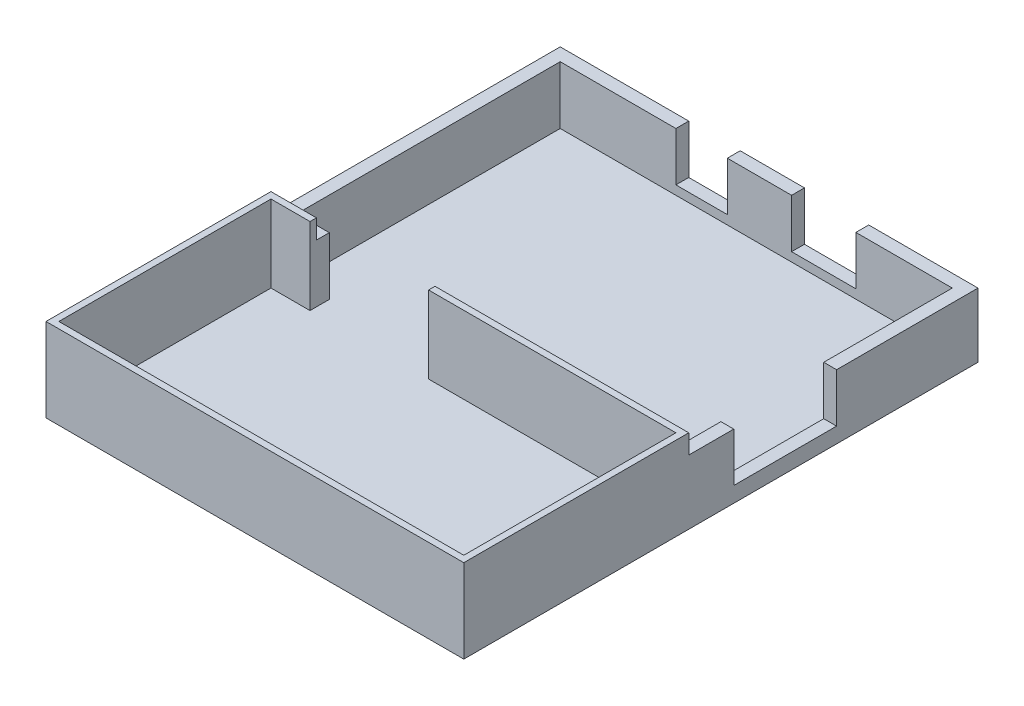
SolidWorks part; units mm, degrees
ref_plane "Front Plane" through (0, 0, 0) normal (0, 0, 1) x (1, 0, 0)
ref_plane "Top Plane" through (0, 0, 0) normal (0, 1, 0) x (1, 0, 0)
ref_plane "Right Plane" through (0, 0, 0) normal (1, 0, 0) x (0, 0, -1)
sketch "Sketch1" plane through (0, 0, 0) normal (0, 1, 0) x (1, 0, 0)
  line L1 (-30.5, -20.5) -> (30.5, -20.5)
  line L2 (-30.5, -20.5) -> (-30.5, 20.5)
  line L3 (-30.5, 20.5) -> (30.5, 20.5)
  line L4 (30.5, -20.5) -> (30.5, 20.5)
  line L5 (-30.5, -20.5) -> (30.5, 20.5) construction
  line L6 (-30.5, 20.5) -> (30.5, -20.5) construction
  point P0 (0, 0)
  dimension "D1" = 61
  dimension "D2" = 41
extrude "Boss-Extrude1" add sketch "Sketch1" along normal blind 1
sketch "Sketch2" plane through (0, 0, 0) normal (0, -1, 0) x (1, 0, 0)
  line L0 (-32.5, -22.5) -> (32.5, -22.5)
  line L1 (32.5, -22.5) -> (32.5, 22.5)
  line L2 (32.5, 22.5) -> (-32.5, 22.5)
  line L3 (-32.5, 22.5) -> (-32.5, -22.5)
  line L4 (30.5, -20.5) -> (30.5, 20.5)
  line L5 (30.5, 20.5) -> (-30.5, 20.5)
  line L6 (-30.5, 20.5) -> (-30.5, -20.5)
  line L7 (-30.5, -20.5) -> (30.5, -20.5)
  line L8 (30.5, -20.5) -> (30.5, 20.5)
  line L9 (30.5, 20.5) -> (-30.5, 20.5)
  line L10 (-30.5, 20.5) -> (-30.5, -20.5)
  line L11 (-30.5, -20.5) -> (30.5, -20.5)
  dimension "D1" = 0
  dimension "D2" = 2
extrude "Boss-Extrude2" add sketch "Sketch2" against normal blind 10
sketch "Sketch3" plane through (0, 10, 0) normal (0, 1, 0) x (1, 0, 0)
  line L0 (-32.5, 22.5) -> (32.5, 22.5) construction
  line L1 (-12.5, 22.5) -> (-4.5, 22.5)
  line L2 (-12.5, 22.5) -> (-12.5, 20.5)
  line L3 (-12.5, 20.5) -> (-4.5, 20.5)
  line L4 (-4.5, 22.5) -> (-4.5, 20.5)
  line L5 (-30.5, 20.5) -> (30.5, 20.5) construction
  line L7 (5.5, 22.5) -> (15.5, 22.5)
  line L8 (5.5, 22.5) -> (5.5, 20.5)
  line L9 (5.5, 20.5) -> (15.5, 20.5)
  line L10 (15.5, 22.5) -> (15.5, 20.5)
  line L11 (32.5, 22.5) -> (32.5, -22.5) construction
  line L12 (32.5, -15.5) -> (30.5, -15.5)
  line L13 (32.5, -15.5) -> (32.5, 0.5)
  line L14 (32.5, 0.5) -> (30.5, 0.5)
  line L15 (30.5, -15.5) -> (30.5, 0.5)
  line L16 (30.5, 20.5) -> (30.5, -20.5) construction
  line L17 (30.5, -20.5) -> (-30.5, -20.5) construction
  line L18 (-30.5, -20.5) -> (-30.5, 20.5) construction
  dimension "D1" = 10
  dimension "D2" = 36
  dimension "D3" = 8
  dimension "D4" = 18
  dimension "D5" = 5
  dimension "D6" = 16
extrude "Cut-Extrude1" cut sketch "Sketch3" against normal offset from surface (7.6 mm away) 1.4 up to face at (0, 1, 0)
sketch "Sketch4" plane through (0, 0, 22.5) normal (0, 0, 1) x (1, 0, 0)
  line L0 (32.5, 10) -> (32.5, 0) construction
  line L1 (-32.5, 0) -> (32.5, 0)
  line L2 (-32.5, 0) -> (-32.5, 1)
  line L3 (-32.5, 1) -> (32.5, 1)
  line L4 (32.5, 0) -> (32.5, 1)
  dimension "D1" = 1
extrude "Boss-Extrude3" add sketch "Sketch4" along normal blind 35
sketch "Sketch5" plane through (0, 1, 0) normal (0, 1, 0) x (1, 0, 0)
  line L0 (-31.5, -23.5) -> (-31.5, -56.5)
  line L1 (-31.5, -56.5) -> (31.5, -56.5)
  line L2 (31.5, -56.5) -> (31.5, -23.5)
  line L3 (31.5, -23.5) -> (-31.5, -23.5)
  line L4 (32.5, -22.5) -> (-32.5, -22.5)
  line L5 (-32.5, -22.5) -> (-32.5, -57.5)
  line L6 (-32.5, -57.5) -> (32.5, -57.5)
  line L7 (32.5, -57.5) -> (32.5, -22.5)
  line L8 (32.5, -22.5) -> (-32.5, -22.5)
  line L9 (-32.5, -22.5) -> (-32.5, -57.5)
  line L10 (-32.5, -57.5) -> (32.5, -57.5)
  line L11 (32.5, -57.5) -> (32.5, -22.5)
  dimension "D1" = 0
  dimension "D2" = 1
extrude "Boss-Extrude4" add sketch "Sketch5" along normal blind 12
sketch "Sketch6" plane through (0, 13, 0) normal (0, 1, 0) x (1, 0, 0)
  line L0 (31.5, -23.5) -> (-31.5, -23.5) construction
  line L1 (-25.4283, -23.5) -> (-6.9775, -23.5)
  line L2 (-25.4283, -23.5) -> (-25.4283, -15.8825)
  line L3 (-25.4283, -15.8825) -> (-6.9775, -15.8825)
  line L4 (-6.9775, -23.5) -> (-6.9775, -15.8825)
extrude "Cut-Extrude2" cut sketch "Sketch6" against normal up to surface (12 mm away) up to face at (0, 1, 40)
